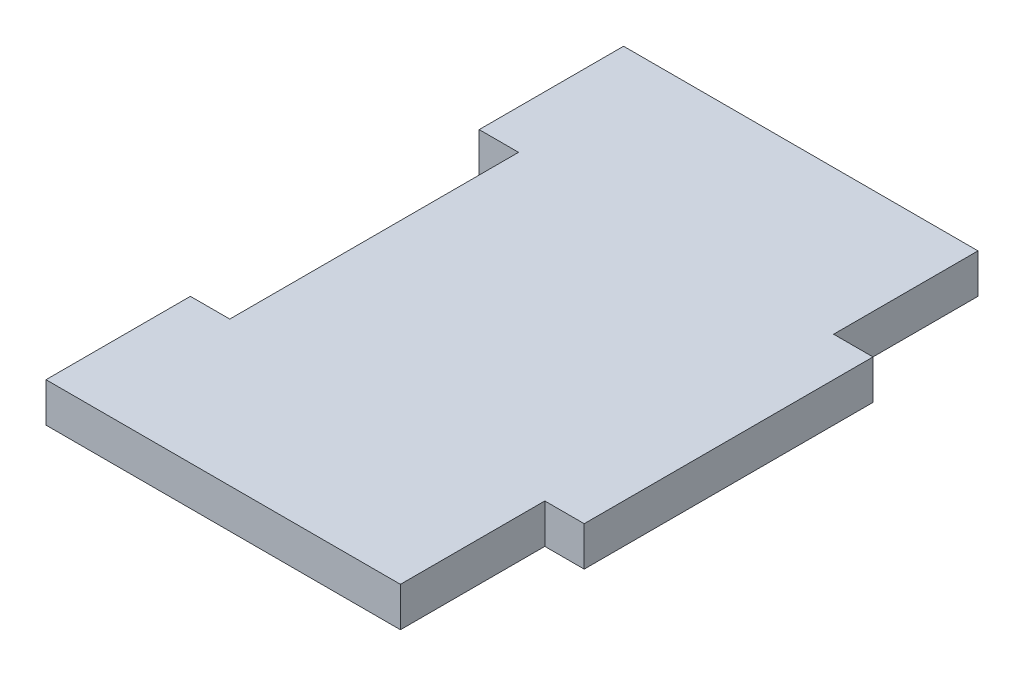
SolidWorks part; units mm, degrees
ref_plane "Alzado" through (0, 0, 0) normal (0, 0, 1) x (1, 0, 0)
ref_plane "Planta" through (0, 0, 0) normal (0, 1, 0) x (1, 0, 0)
ref_plane "Vista lateral" through (0, 0, 0) normal (1, 0, 0) x (0, 0, -1)
sketch "Croquis1" plane through (0, 0, 0) normal (0, 1, 0) x (1, 0, 0)
  line L0 (0, 0) -> (0, 11)
  line L1 (0, 0) -> (27, 0)
  line L2 (30, 11) -> (30, 33)
  line L3 (27, 44) -> (0, 44)
  line L5 (3, 22) -> (3, 33)
  line L6 (3, 33) -> (0, 33)
  line L7 (3, 22) -> (3, 11)
  line L8 (3, 11) -> (0, 11)
  line L9 (30, 22) -> (30, 33)
  line L10 (30, 33) -> (27, 33)
  line L11 (27, 33) -> (27, 44)
  line L12 (30, 22) -> (30, 11)
  line L13 (30, 11) -> (27, 11)
  line L14 (27, 11) -> (27, 0)
  line L15 (0, 33) -> (0, 44)
  dimension "D1" = 44
  dimension "D4" = 11
  dimension "D5" = 11
  dimension "D6" = 3
extrude "Saliente-Extruir1" add sketch "Croquis1" along normal blind 3 contours L15 L6 L5 L7 L8 L0 L1 L14 L13 L2 L10 L11 L3
